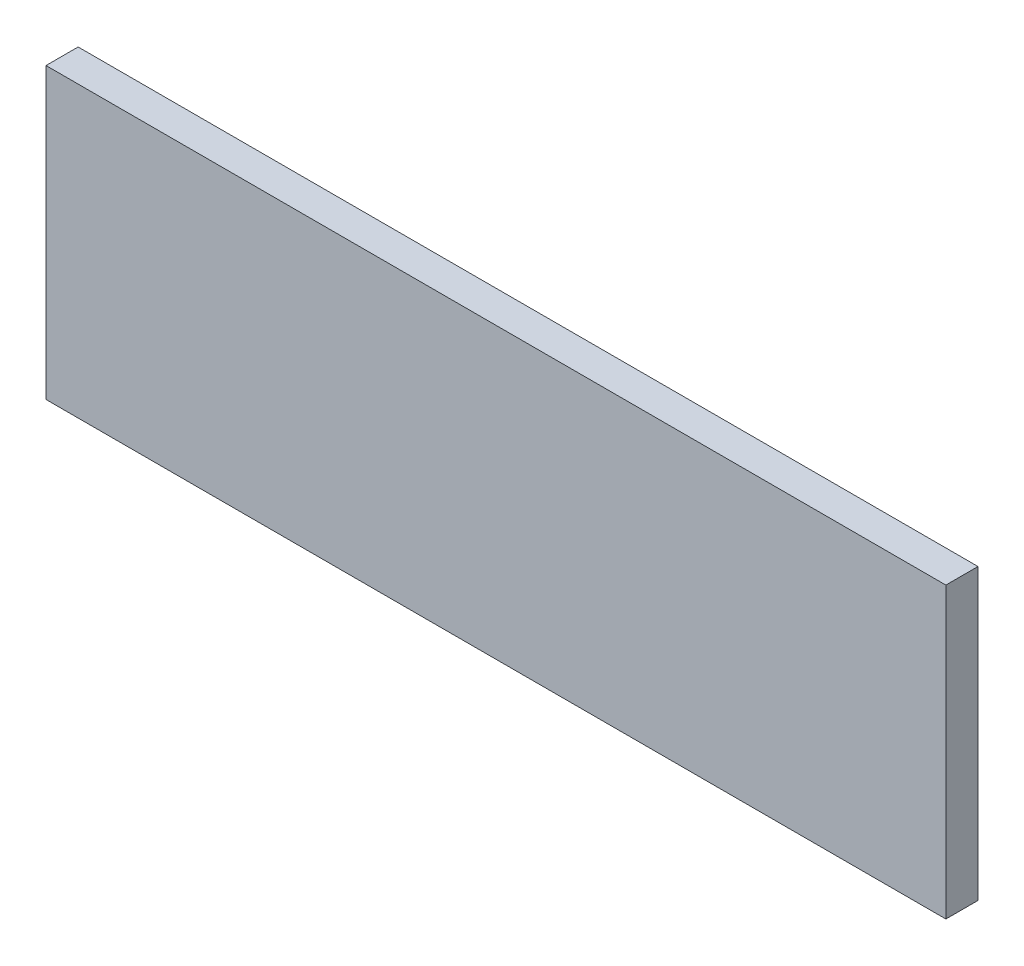
SolidWorks part; units mm, degrees
ref_plane "Front Plane" through (0, 0, 0) normal (0, 0, 1) x (1, 0, 0)
ref_plane "Top Plane" through (0, 0, 0) normal (0, 1, 0) x (1, 0, 0)
ref_plane "Right Plane" through (0, 0, 0) normal (1, 0, 0) x (0, 0, -1)
sketch "Sketch1" plane through (0, 0, 0) normal (0, 0, 1) x (1, 0, 0)
  line L1 (0, 0) -> (355.6, 0)
  line L2 (0, 0) -> (0, 114.3)
  line L3 (0, 114.3) -> (355.6, 114.3)
  line L4 (355.6, 0) -> (355.6, 114.3)
  dimension "D1" = 355.6
  dimension "D2" = 114.3
extrude "Boss-Extrude1" add sketch "Sketch1" along normal blind 12.7
